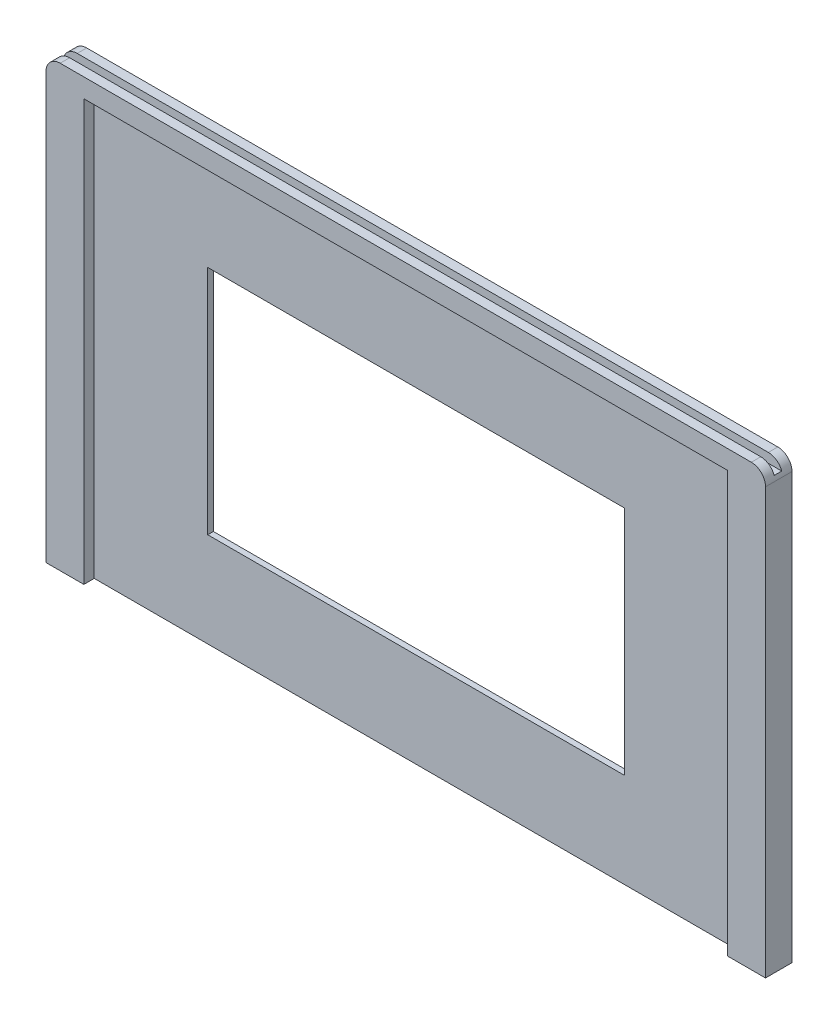
SolidWorks part; units mm, degrees
ref_plane "前视基准面" through (0, 0, 0) normal (0, 0, 1) x (1, 0, 0)
ref_plane "上视基准面" through (0, 0, 0) normal (0, 1, 0) x (1, 0, 0)
ref_plane "右视基准面" through (0, 0, 0) normal (1, 0, 0) x (0, 0, -1)
other "Configuration Table"
sketch "草图1" plane through (0, 0, 0) normal (0, 0, 1) x (1, 0, 0)
  line L0 (-91.35, 69.4698) -> (91.35, 69.4698)
  line L1 (95.1, 65.7198) -> (95.1, -46.7302)
  line L2 (-95.1, 65.7198) -> (-95.1, -46.7302)
  line L3 (-95.1, -46.7302) -> (95.1, -46.7302)
  arc A0 (-91.35, 69.4698) -> (-95.1, 65.7198) centre (-91.35, 65.7198) ccw
  arc A1 (95.1, 65.7198) -> (91.35, 69.4698) centre (91.35, 65.7198) ccw
  point P2 (0, 69.4698)
  dimension "D3" = 7.5
  dimension "D1" = 7.5
  dimension "D2" = 190.2
  dimension "D4" = 116.2
extrude "凸台-拉伸1" add sketch "草图1" along normal blind 7
sketch "草图2" plane through (0, 0, 0) normal (0, 0, 1) x (1, 0, 0)
  line L0 (-85.1, -46.7302) -> (85.1, -46.7302)
  line L4 (-85.1, -36.7302) -> (-85.1, -46.7302)
  line L5 (-95.1, -46.7302) -> (95.1, -46.7302) construction
  line L6 (85.1, -36.7302) -> (85.1, -46.7302)
  line L7 (-85.1, 59.4698) -> (-85.1, 64.4698)
  line L8 (-85.1, -36.7302) -> (85.1, -36.7302)
  line L9 (85.1, -36.7302) -> (85.1, 59.4698)
  line L10 (85.1, 59.4698) -> (-85.1, 59.4698)
  line L11 (-85.1, 59.4698) -> (-85.1, -36.7302)
  line L13 (85.1, -36.7302) -> (85.1, 59.4698)
  line L15 (-85.1, 59.4698) -> (-85.1, -36.7302)
  line L16 (85.1, 59.4698) -> (85.1, 64.4698)
  line L17 (-85.1, 64.4698) -> (85.1, 64.4698)
  dimension "D2" = 5
  dimension "D1" = 10
extrude "切除-拉伸1" cut sketch "草图2" along normal blind 2.75
sketch "草图3" plane through (0, 0, 7) normal (0, 0, 1) x (1, 0, 0)
  line L6 (-85.1, -36.7302) -> (-85.1, -46.7302)
  line L7 (85.1, -36.7302) -> (85.1, -46.7302)
  line L8 (-95.1, -46.7302) -> (95.1, -46.7302) construction
  line L9 (-85.1, 59.4698) -> (-85.1, 64.4698)
  line L10 (-85.1, -36.7302) -> (85.1, -36.7302)
  line L11 (85.1, -36.7302) -> (85.1, 59.4698)
  line L12 (85.1, 59.4698) -> (-85.1, 59.4698)
  line L13 (-85.1, 59.4698) -> (-85.1, -36.7302)
  line L15 (85.1, -36.7302) -> (85.1, 59.4698)
  line L17 (-85.1, 59.4698) -> (-85.1, -36.7302)
  line L18 (-85.1, 64.4698) -> (85.1, 64.4698)
  line L19 (85.1, 64.4698) -> (85.1, 59.4698)
  line L20 (-85.1, -46.7302) -> (85.1, -46.7302)
  dimension "D2" = 5
  dimension "D1" = 10
extrude "切除-拉伸2" cut sketch "草图3" against normal blind 2.75
sketch "草图4" plane through (0, 69.4698, 0) normal (0, 1, 0) x (1, 0, 0)
  line L0 (-95.1, -2.5) -> (-95.1, -4.5)
  line L1 (-95.1, -4.5) -> (95.1, -4.5)
  line L2 (95.1, -4.5) -> (95.1, -2.5)
  line L3 (95.1, -2.5) -> (-95.1, -2.5)
  line L8 (-95.1, -7) -> (-95.1, 0) construction
  line L17 (95.1, -7) -> (95.1, 0) construction
  point P6 (-95.1, -3.5)
  dimension "D1" = 2
extrude "切除-拉伸3" cut sketch "草图4" against normal blind 2.5
sketch "草图5" plane through (0, 0, 4.25) normal (0, 0, 1) x (1, 0, 0)
  line L0 (-55.1, 39.4698) -> (55.1, 39.4698)
  line L1 (55.1, 39.4698) -> (55.1, -21.7302)
  line L2 (55.1, -21.7302) -> (-55.1, -21.7302)
  line L3 (-55.1, -21.7302) -> (-55.1, 39.4698)
  line L4 (-85.1, 64.4698) -> (-85.1, -46.7302) construction
  line L5 (85.1, -46.7302) -> (85.1, 64.4698) construction
  line L6 (85.1, 64.4698) -> (-85.1, 64.4698) construction
  line L7 (-85.1, -46.7302) -> (85.1, -46.7302) construction
  dimension "D1" = 30
  dimension "D2" = 30
  dimension "D3" = 25
  dimension "D4" = 25
extrude "切除-拉伸4" cut sketch "草图5" against normal through all
